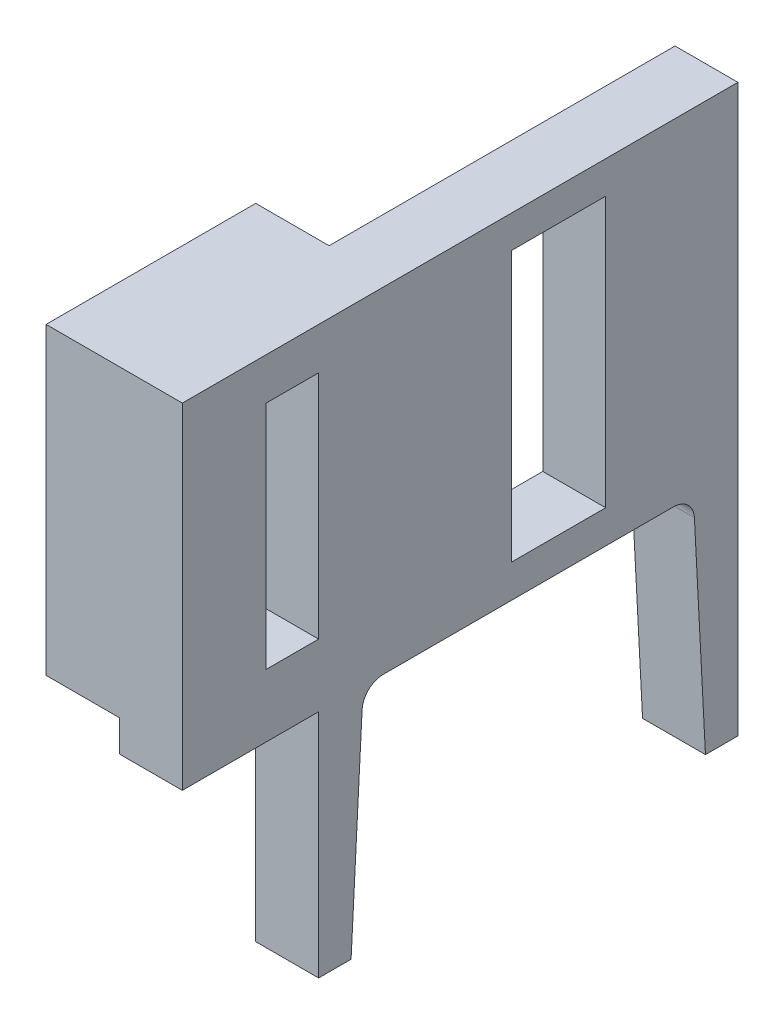
SolidWorks part; units mm, degrees
ref_plane "Front Plane" through (0, 0, 0) normal (0, 0, 1) x (1, 0, 0)
ref_plane "Top Plane" through (0, 0, 0) normal (0, 1, 0) x (1, 0, 0)
ref_plane "Right Plane" through (0, 0, 0) normal (1, 0, 0) x (0, 0, -1)
sketch "Sketch1" plane through (0, 0, 0) normal (1, 0, 0) x (0, 0, -1)
  line L1 (-26.5, 16) -> (26.5, 16)
  line L2 (-26.5, 16) -> (-26.5, -16)
  line L3 (-26.5, -16) -> (26.5, -16)
  line L4 (26.5, 16) -> (26.5, -16)
  line L5 (-26.5, 16) -> (26.5, -16) construction
  line L6 (-26.5, -16) -> (26.5, 16) construction
  point P0 (0, 0)
  dimension "D1" = 53
  dimension "D2" = 32
extrude "Boss-Extrude1" add sketch "Sketch1" along normal blind 13
sketch "Sketch7" plane through (0, 16, 0) normal (0, 1, 0) x (1, 0, 0)
  line L1 (0, 26.5) -> (7, 26.5)
  line L2 (0, 26.5) -> (0, -13.5)
  line L3 (0, -13.5) -> (7, -13.5)
  line L4 (7, 26.5) -> (7, -13.5)
  dimension "D1" = 40
  dimension "D2" = 7
extrude "Cut-Extrude3" cut sketch "Sketch7" against normal through all
sketch "Sketch19" plane through (0, -16, 0) normal (0, -1, 0) x (-1, 0, 0)
  line L0 (-7, -13.5) -> (-7, 26.5) construction
  line L1 (-13, 26.5) -> (-7, 26.5)
  line L2 (-13, 26.5) -> (-13, 22.25)
  line L3 (-13, 22.25) -> (-7, 22.25)
  line L4 (-7, 26.5) -> (-7, 22.25)
  line L5 (-13, -26.5) -> (-13, 26.5) construction
  line L6 (-7, -13.5) -> (-13, -13.5)
  line L7 (-7, -13.5) -> (-7, -9.25)
  line L8 (-7, -9.25) -> (-13, -9.25)
  line L9 (-13, -13.5) -> (-13, -9.25)
  dimension "D1" = 4.25
  dimension "D2" = 4.25
sketch "Sketch8" plane through (0, -16, 0) normal (0, -1, 0) x (1, 0, 0)
  line L1 (13, -26.5) -> (7, -26.5)
  line L2 (13, -26.5) -> (13, 13.5)
  line L3 (13, 13.5) -> (7, 13.5)
  line L4 (7, -26.5) -> (7, 13.5)
extrude "Boss-Extrude2" add sketch "Sketch8" along normal blind 22
sketch "Sketch20" plane through (0, -16, 0) normal (0, -1, 0) x (-1, 0, 0)
  line L1 (-13, -9.25) -> (-7, -9.25)
  line L2 (-13, -9.25) -> (-13, 22.25)
  line L3 (-13, 22.25) -> (-7, 22.25)
  line L4 (-7, -9.25) -> (-7, 22.25)
extrude "Cut-Extrude9" cut sketch "Sketch20" along normal through all draft 3 draft outward yes
fillet "Fillet1" radius 2 1 edges at (10, -16, -22.25)
fillet "Fillet2" radius 2 1 edges at (10, -16, 9.25)
sketch "Sketch49" plane through (0, 0, 13.5) normal (0, 0, -1) x (-1, 0, 0)
  line L1 (-7, -16) -> (0, -16)
  line L2 (-7, -16) -> (-7, 16)
  line L3 (-7, 16) -> (0, 16)
  line L4 (0, -16) -> (0, 16)
extrude "Boss-Extrude3" add sketch "Sketch49" along normal blind 7
sketch "Sketch50" plane through (0, -16, 0) normal (0, -1, 0) x (1, 0, 0)
  line L1 (7, 6.5) -> (0, 6.5)
  line L2 (7, 6.5) -> (7, 26.5)
  line L3 (7, 26.5) -> (0, 26.5)
  line L4 (0, 6.5) -> (0, 26.5)
extrude "Cut-Extrude19" cut sketch "Sketch50" against normal blind 3
sketch "Sketch35" plane through (7, 0, 0) normal (-1, 0, 0) x (0, 0, 1)
  line L1 (-13.8814, 12.9016) -> (-4.8814, 12.9016)
  line L2 (-13.8814, 12.9016) -> (-13.8814, -12.8405)
  line L3 (-13.8814, -12.8405) -> (-4.8814, -12.8405)
  line L4 (-4.8814, 12.9016) -> (-4.8814, -12.8405)
  dimension "D1" = 9
extrude "Cut-Extrude15" cut sketch "Sketch35" against normal through all
sketch "Sketch36" plane through (7, 0, 0) normal (-1, 0, 0) x (0, 0, 1)
  line L1 (-3.6189, 12.6982) -> (4.8929, 12.6982)
  line L2 (-3.6189, 12.6982) -> (-3.6189, -13)
  line L3 (-3.6189, -13) -> (4.8929, -13)
  line L4 (4.8929, 12.6982) -> (4.8929, -13)
extrude "Cut-Extrude16" cut sketch "Sketch36" against normal blind 5
sketch "Sketch51" plane through (7, 0, 0) normal (-1, 0, 0) x (0, 0, 1)
  line L0 (7.3521, -16) -> (-20.3521, -16) construction
  line L1 (-26.5, 16) -> (-24.5, 16)
  line L2 (-26.5, 16) -> (-26.5, -16)
  line L3 (-26.5, -16) -> (-24.5, -16)
  line L4 (-24.5, 16) -> (-24.5, -16)
  dimension "D1" = 2
sketch "Sketch52" plane through (7, 0, 0) normal (-1, 0, 0) x (0, 0, 1)
  line L0 (7.3521, -16) -> (-20.3521, -16) construction
  line L1 (-13.8814, 12.9016) -> (-15.8814, 12.9016)
  line L2 (-13.8814, 12.9016) -> (-13.8814, -16)
  line L3 (-13.8814, -16) -> (-15.8814, -16)
  line L4 (-15.8814, 12.9016) -> (-15.8814, -16)
  dimension "D1" = 2
sketch "Sketch54" plane through (7, 0, 0) normal (-1, 0, 0) x (0, 0, 1)
  line L1 (4.8929, -13) -> (-26.5, -13)
  line L2 (4.8929, -13) -> (4.8929, -16)
  line L3 (4.8929, -16) -> (-26.5, -16)
  line L4 (-26.5, -13) -> (-26.5, -16)
sketch "Sketch55" plane through (7, 0, 0) normal (-1, 0, 0) x (0, 0, 1)
  line L1 (-15.8814, 12.9016) -> (-24.5316, 12.9016)
  line L2 (-15.8814, 12.9016) -> (-15.8814, -13.1088)
  line L3 (-15.8814, -13.1088) -> (-24.5316, -13.1088)
  line L4 (-24.5316, 12.9016) -> (-24.5316, -13.1088)
extrude "Cut-Extrude20" cut sketch "Sketch55" against normal blind 5
sketch "Sketch56" plane through (0, 0, 0) normal (-1, 0, 0) x (0, 0, 1)
  line L1 (6.5, 16) -> (13.5, 16)
  line L2 (6.5, 16) -> (6.5, -13)
  line L3 (6.5, -13) -> (13.5, -13)
  line L4 (13.5, 16) -> (13.5, -13)
  point P5 (0, 0)
  dimension "D1" = 7
sketch "Sketch61" plane through (0, 0, 0) normal (-1, 0, 0) x (0, 0, 1)
  line L1 (13.5, -13) -> (26.5, -13)
  line L2 (13.5, -13) -> (13.5, -10)
  line L3 (13.5, -10) -> (26.5, -10)
  line L4 (26.5, -13) -> (26.5, -10)
  dimension "D1" = 13
  dimension "D2" = 3
sketch "Sketch62" plane through (0, 0, 0) normal (-1, 0, 0) x (0, 0, 1)
  line L0 (26.5, 16) -> (26.5, -13) construction
  line L1 (13.5, 16) -> (26.5, 16)
  line L2 (13.5, 16) -> (13.5, 12)
  line L3 (13.5, 12) -> (26.5, 12)
  line L4 (26.5, 16) -> (26.5, 12)
  dimension "D1" = 4
sketch "Sketch63" plane through (0, 0, 0) normal (-1, 0, 0) x (0, 0, 1)
  line L1 (13.5, 12) -> (18.5, 12)
  line L2 (13.5, 12) -> (13.5, -10)
  line L3 (13.5, -10) -> (18.5, -10)
  line L4 (18.5, 12) -> (18.5, -10)
  dimension "D1" = 5
  dimension "D2" = 22
extrude "Cut-Extrude21" cut sketch "Sketch63" against normal through all
